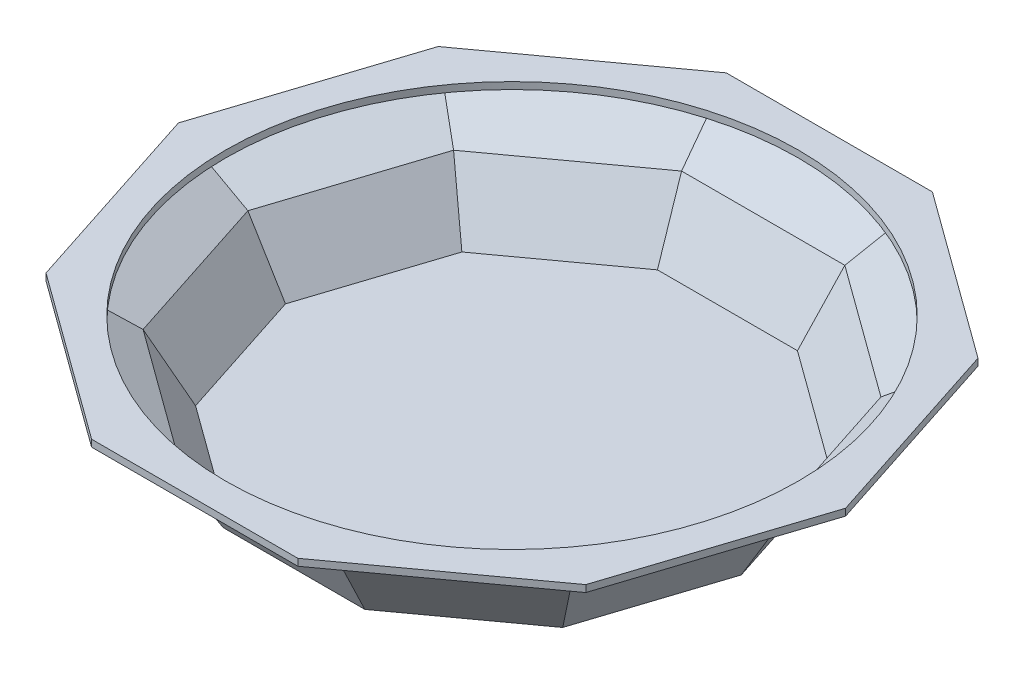
SolidWorks part; units mm, degrees
ref_plane "Front Plane" through (0, 0, 0) normal (0, 0, 1) x (1, 0, 0)
ref_plane "Top Plane" through (0, 0, 0) normal (0, 1, 0) x (1, 0, 0)
ref_plane "Right Plane" through (0, 0, 0) normal (1, 0, 0) x (0, 0, -1)
sketch "Sketch4" plane through (0, 0, 0) normal (0, 1, 0) x (1, 0, 0)
  line L0 (30.9017, -95.1057) -> (80.9017, -58.7785)
  line L1 (100, 0) -> (80.9017, 58.7785)
  line L2 (80.9017, 58.7785) -> (30.9017, 95.1057)
  line L3 (30.9017, 95.1057) -> (-30.9017, 95.1057)
  line L4 (-30.9017, 95.1057) -> (-80.9017, 58.7785)
  line L5 (-80.9017, 58.7785) -> (-100, 0)
  line L6 (-100, 0) -> (-80.9017, -58.7785)
  line L7 (-80.9017, -58.7785) -> (-30.9017, -95.1057)
  line L8 (-30.9017, -95.1057) -> (30.9017, -95.1057)
  line L9 (80.9017, -58.7785) -> (100, 0)
  circle A0 centre (0, 0) radius 95.1057 construction
  dimension "D1" = 100
extrude "Stage1Ex" add sketch "Sketch4" along normal blind 30 draft 30 draft outward yes
sketch "Sketch7" plane through (0, 30, 0) normal (0, 1, 0) x (1, 0, 0)
  line L1 (-115.2119, 0) -> (-93.2084, -67.7198)
  line L2 (-93.2084, -67.7198) -> (-35.6024, -109.573)
  line L3 (-35.6024, -109.573) -> (35.6024, -109.573)
  line L4 (35.6024, -109.573) -> (93.2084, -67.7198)
  line L5 (93.2084, -67.7198) -> (115.2119, 0)
  line L6 (115.2119, 0) -> (93.2084, 67.7198)
  line L7 (93.2084, 67.7198) -> (35.6024, 109.573)
  line L8 (35.6024, 109.573) -> (-35.6024, 109.573)
  line L9 (-35.6024, 109.573) -> (-93.2084, 67.7198)
  line L10 (-93.2084, 67.7198) -> (-115.2119, 0)
  circle A0 centre (0, 0) radius 109.573 construction
  point P15 (75.2674, 0)
  dimension "D1" = 3
extrude "Stage1In" cut sketch "Sketch7" against normal blind 27 draft 30
sketch "Sketch8" plane through (0, 30, 0) normal (0, 1, 0) x (1, 0, 0)
  line L1 (36.5295, 112.4262) -> (-36.5295, 112.4262)
  line L2 (-36.5295, 112.4262) -> (-95.6354, 69.4832)
  line L3 (-95.6354, 69.4832) -> (-118.2119, 0)
  line L4 (-118.2119, 0) -> (-95.6354, -69.4832)
  line L5 (-95.6354, -69.4832) -> (-36.5295, -112.4262)
  line L6 (-36.5295, -112.4262) -> (36.5295, -112.4262)
  line L7 (36.5295, -112.4262) -> (95.6354, -69.4832)
  line L8 (95.6354, -69.4832) -> (118.2119, 0)
  line L9 (118.2119, 0) -> (95.6354, 69.4832)
  line L10 (95.6354, 69.4832) -> (36.5295, 112.4262)
  circle A0 centre (0, 0) radius 112.4262 construction
  point P1 (64.3087, 46.723)
extrude "Stage2Ex" add sketch "Sketch8" along normal blind 15 draft 60 draft outward yes
sketch "Sketch10" plane through (0, 45, 0) normal (0, 1, 0) x (1, 0, 0)
  line L1 (115.3089, -83.7768) -> (142.5296, 0)
  line L2 (142.5296, 0) -> (115.3089, 83.7768)
  line L3 (115.3089, 83.7768) -> (44.0441, 135.5538)
  line L4 (44.0441, 135.5538) -> (-44.0441, 135.5538)
  line L5 (-44.0441, 135.5538) -> (-115.3089, 83.7768)
  line L6 (-115.3089, 83.7768) -> (-142.5296, 0)
  line L7 (-142.5296, 0) -> (-115.3089, -83.7768)
  line L8 (-115.3089, -83.7768) -> (-44.0441, -135.5538)
  line L9 (-44.0441, -135.5538) -> (44.0441, -135.5538)
  line L10 (44.0441, -135.5538) -> (115.3089, -83.7768)
  circle A0 centre (0, 0) radius 135.5538 construction
  point P1 (32.607, -100.4513)
  point P14 (76.3673, -57.8982)
  point P15 (0, 0)
  point P16 (-34.6755, -102.561)
  point P17 (87.4952, -63.8435)
  point P19 (45.8982, -141.2601)
  point P20 (114.9029, -82.8872)
  point P21 (111.7062, 79.6537)
  point P22 (140.2142, 0)
  dimension "D1" = 3
extrude "Stage2In" cut sketch "Sketch10" against normal blind 20 draft 60
sketch "Sketch11" plane through (0, 45, 0) normal (0, 1, 0) x (1, 0, 0)
  line L1 (117.736, -85.5402) -> (145.5296, 0)
  line L2 (145.5296, 0) -> (117.736, 85.5402)
  line L3 (117.736, 85.5402) -> (44.9711, 138.4069)
  line L4 (44.9711, 138.4069) -> (-44.9711, 138.4069)
  line L5 (-44.9711, 138.4069) -> (-117.736, 85.5402)
  line L6 (-117.736, 85.5402) -> (-145.5296, 0)
  line L7 (-145.5296, 0) -> (-117.736, -85.5402)
  line L8 (-117.736, -85.5402) -> (-44.9711, -138.4069)
  line L9 (-44.9711, -138.4069) -> (44.9711, -138.4069)
  line L10 (44.9711, -138.4069) -> (117.736, -85.5402)
  circle A0 centre (0, 0) radius 125
  circle A1 centre (0, 0) radius 138.4069 construction
  point P2 (0, 0)
  point P3 (0, 0)
  point P15 (0, 0)
  point P16 (0, 0)
  point P17 (-122.8228, -88.9428)
  point P19 (0, 0)
  point P20 (-122.5439, -89.3266)
  point P21 (0, 0)
  point P22 (0, 0)
  point P23 (-125.1028, -90.8925)
  point P25 (0, 0)
  dimension "D1" = 250
extrude "Boss-Extrude6" add sketch "Sketch11" along normal blind 3
equation "\"GeneralThickness\"= 3"
equation "\"D1@Sketch7\"=\"GeneralThickness\""
equation "\"D1@Boss-Extrude6\"=\"GeneralThickness\""
equation "\"D2@Boss-Extrude6\"=\"GeneralThickness\""
equation "\"D1@Sketch10\"=\"GeneralThickness\""
